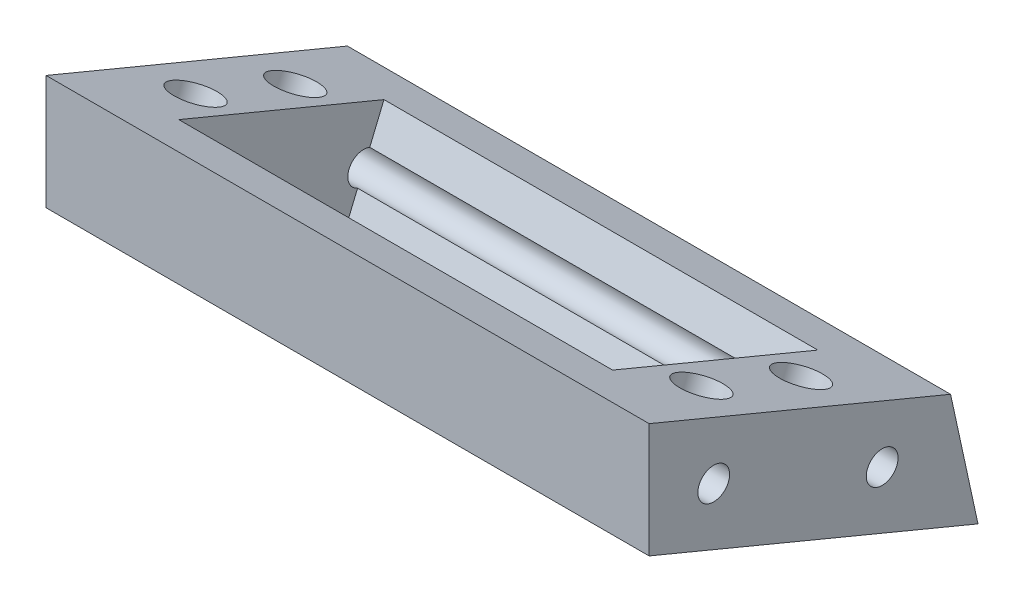
SolidWorks part; units mm, degrees
ref_plane "Alzado" through (0, 0, 0) normal (0, 0, 1) x (1, 0, 0)
ref_plane "Planta" through (0, 0, 0) normal (0, 1, 0) x (1, 0, 0)
ref_plane "Vista lateral" through (0, 0, 0) normal (1, 0, 0) x (0, 0, -1)
sketch "Croquis1" plane through (0, 0, 0) normal (1, 0, 0) x (0, 0, -1)
  line L0 (-1.6849, 59.6161) -> (-1.6849, 70.4452)
  line L1 (29.3937, 46.7008) -> (26.8027, 58.6066)
  line L2 (-1.6849, 70.4452) -> (26.8027, 58.6066)
  line L7 (-1.6849, 59.6161) -> (29.3937, 46.7008)
extrude "Saliente-Extruir1" add sketch "Croquis1" along normal blind 57
sketch "Croquis2" plane through (0, 59.474, -24.7155) normal (0, 0.9234, -0.3838) x (1, 0, 0)
  line L0 (0, -13.1645) -> (57, -13.1645) construction
  line L1 (0, 2.2603) -> (0, -28.5893) construction
  line L2 (57, 2.2603) -> (57, -28.5893) construction
  line L3 (28.5, -28.5893) -> (28.5, -4.8753) construction
  line L4 (57, -28.5893) -> (0, -28.5893) construction
  line L6 (8, -23.6645) -> (49, -23.6645)
  line L7 (8, -23.6645) -> (8, -2.6645)
  line L8 (8, -2.6645) -> (49, -2.6645)
  line L9 (49, -23.6645) -> (49, -2.6645)
  line L10 (8, -23.6645) -> (49, -2.6645) construction
  line L11 (8, -2.6645) -> (49, -23.6645) construction
  point P10 (28.5, -13.1645)
  dimension "D1" = 41
  dimension "D2" = 21
extrude "Cortar-Extruir1" cut sketch "Croquis2" against normal blind 40
sketch "Croquis3" plane through (0, 0, 0) normal (-1, 0, 0) x (0, 0, 1)
  line L0 (-28.0982, 52.6537) -> (1.6849, 65.0306) construction
  line L1 (-29.3937, 46.7008) -> (-26.8027, 58.6066) construction
  line L2 (1.6849, 70.4452) -> (1.6849, 59.6161) construction
  circle A0 centre (-20.3377, 55.8787) radius 1.5
  circle A1 centre (-4.4197, 62.4938) radius 1.5
  dimension "D1" = 3
  dimension "D2" = 3
extrude "Cortar-Extruir2" cut sketch "Croquis3" against normal through all
sketch "Croquis4" plane through (0, 59.474, -24.7155) normal (0, 0.9234, -0.3838) x (1, 0, 0)
  circle A0 centre (4.6, -18.2645) radius 2.2
  circle A1 centre (4.6, -8.0645) radius 2.2
  circle A2 centre (52.4, -18.2645) radius 2.2
  circle A3 centre (52.4, -8.0645) radius 2.2
extrude "Cortar-Extruir3" cut sketch "Croquis4" against normal blind 95
